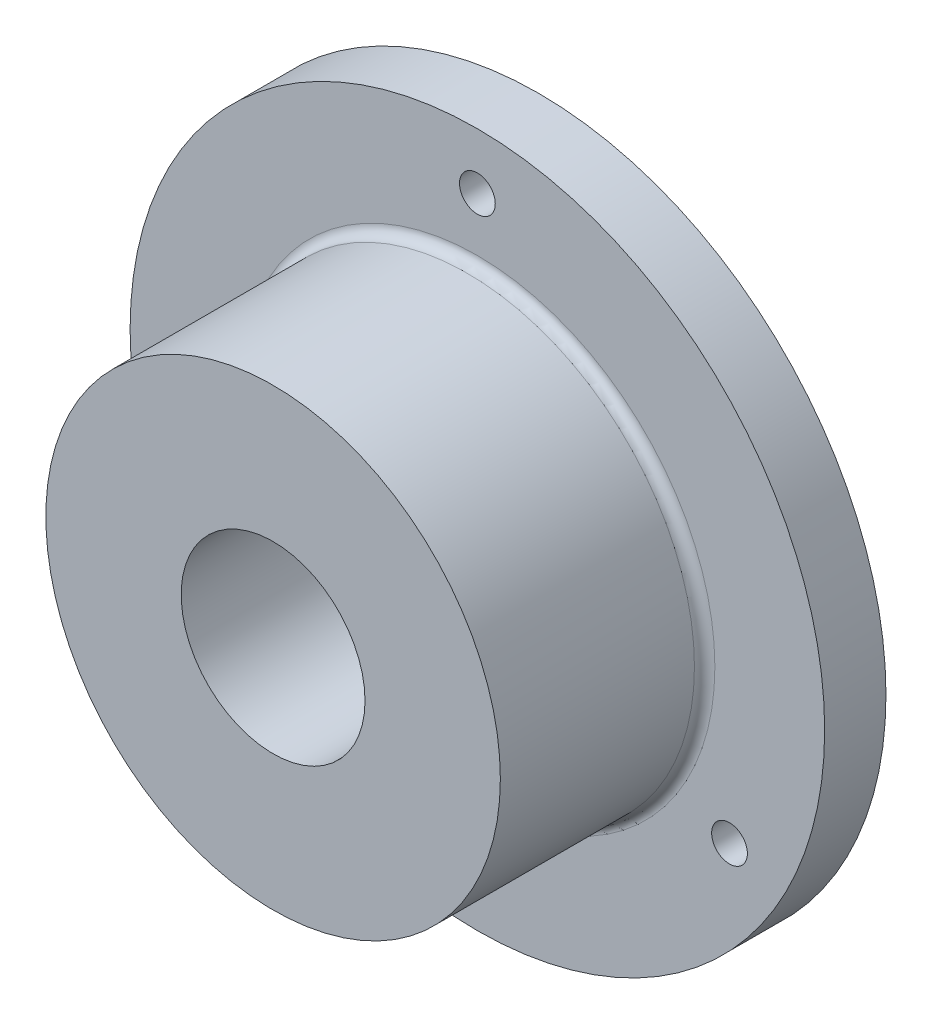
SolidWorks part; units mm, degrees
ref_plane "前视基准面" through (0, 0, 0) normal (0, 0, 1) x (1, 0, 0)
ref_plane "上视基准面" through (0, 0, 0) normal (0, 1, 0) x (1, 0, 0)
ref_plane "右视基准面" through (0, 0, 0) normal (1, 0, 0) x (0, 0, -1)
sketch "草图1" plane through (0, 0, 0) normal (0, 0, 1) x (1, 0, 0)
  circle A0 centre (0, 0) radius 34
  dimension "D1" = 68
extrude "底" add sketch "草图1" along normal blind 6
sketch "草图2" plane through (0, 0, 6) normal (0, 0, 1) x (1, 0, 0)
  circle A0 centre (0, 0) radius 22.25
  dimension "D1" = 44.5
extrude "台" add sketch "草图2" along normal blind 20
sketch "草图3" plane through (0, 0, 26) normal (0, 0, 1) x (1, 0, 0)
  circle A0 centre (0, 0) radius 9
  dimension "D1" = 18
sketch "草图4" plane through (0, 0, 6) normal (0, 0, 1) x (1, 0, 0)
  line L0 (0, 22.25) -> (0, 28.5) construction
  line L1 (0, 28.5) -> (0, 34) construction
  circle A0 centre (0, 0) radius 28.5 construction
  circle A1 centre (0, 0) radius 22.25 construction
  circle A2 centre (0, 0) radius 22.25 construction
  circle A3 centre (0, 0) radius 34 construction
  circle A4 centre (0, 28.5) radius 1.75
  circle A5 centre (24.6817, -14.25) radius 1.75
  circle A6 centre (-24.6817, -14.25) radius 1.75
  point P21 (0, 0)
  dimension "D1" = 3.5
  dimension "D5" = 57
  dimension "D4" = 5.5
  dimension "D2" = 3
extrude "安装孔" cut sketch "草图4" against normal through all
fillet "圆角1" radius 1 1 edges at (22.25, 0, 6)
extrude "通孔" cut sketch "草图3" against normal through all both and the other way through all
